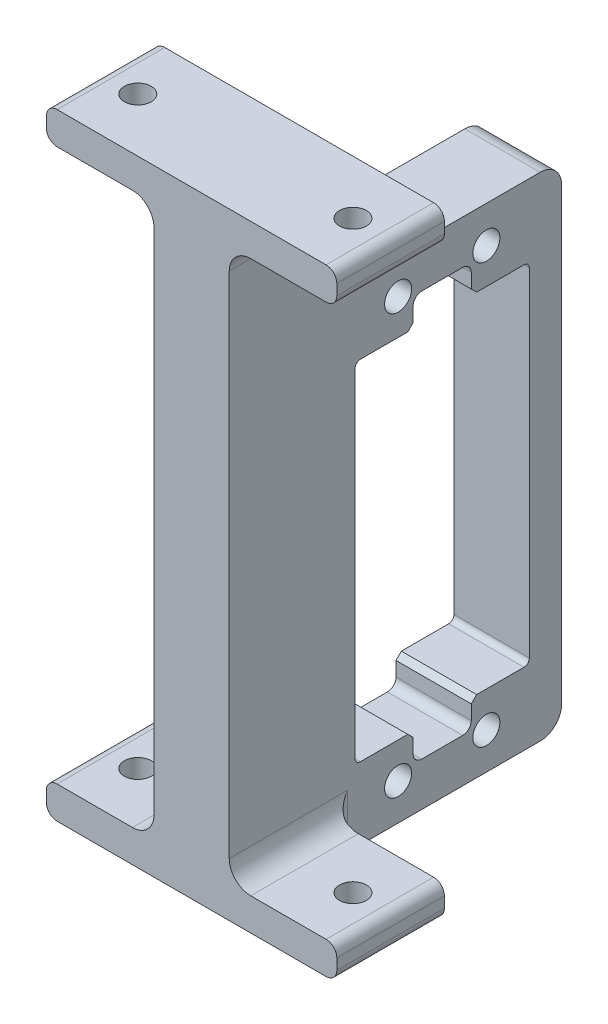
SolidWorks part; units mm, degrees
material "PLA"
ref_plane "Front Plane" through (0, 0, 0) normal (0, 0, 1) x (1, 0, 0)
ref_plane "Top Plane" through (0, 0, 0) normal (0, 1, 0) x (1, 0, 0)
ref_plane "Right Plane" through (0, 0, 0) normal (1, 0, 0) x (0, 0, -1)
sketch "Sketch1" plane through (0, 0, 0) normal (0, 0, 1) x (1, 0, 0)
  line L0 (17.145, 0) -> (-17.145, 0)
  line L1 (-17.145, 0) -> (-17.145, 3.81)
  line L2 (-17.145, 3.81) -> (-4.445, 3.81)
  line L3 (-4.445, 3.81) -> (-4.445, 68.961)
  line L11 (-4.445, 36.3855) -> (4.445, 36.3855) construction
  line L18 (4.445, 3.81) -> (4.445, 68.961)
  line L19 (17.145, 3.81) -> (4.445, 3.81)
  line L20 (17.145, 0) -> (17.145, 3.81)
  line L21 (17.145, 68.961) -> (4.445, 68.961)
  line L22 (17.145, 72.771) -> (17.145, 68.961)
  line L23 (17.145, 72.771) -> (-17.145, 72.771)
  line L24 (-17.145, 72.771) -> (-17.145, 68.961)
  line L25 (-17.145, 68.961) -> (-4.445, 68.961)
  dimension "D1" = 8.89
  dimension "D2" = 3.81
  dimension "D3" = 3.81
  dimension "D4" = 72.771
  dimension "D5" = 34.29
extrude "Frame_Mount" add sketch "Sketch1" along normal blind 12.7
sketch "Sketch3" plane through (0, 0, 0) normal (0, -1, 0) x (1, 0, 0)
  line L0 (17.145, 6.35) -> (-17.145, 6.35) construction
  line L1 (17.145, 12.7) -> (17.145, 0) construction
  line L2 (-17.145, 12.7) -> (-17.145, 0) construction
  line L3 (0, 0) -> (0, 12.7) construction
  line L4 (-17.145, 12.7) -> (17.145, 12.7) construction
  circle A0 centre (12.7, 6.35) radius 1.5875
  circle A1 centre (-12.7, 6.35) radius 1.5875
  dimension "D1" = 3.175
  dimension "D2" = 25.4
extrude "Mount_Holes" cut sketch "Sketch3" against normal through all
sketch "Sketch4" plane through (4.445, 0, 0) normal (1, 0, 0) x (0, 0, -1)
  line L1 (2.159, 49.657) -> (22.733, 49.657)
  line L2 (2.159, 49.657) -> (2.159, 8.509)
  line L3 (2.159, 8.509) -> (22.733, 8.509)
  line L4 (22.733, 49.657) -> (22.733, 8.509)
  line L5 (-12.7, 0) -> (0, 0) construction
  line L6 (0, 58.166) -> (26.543, 58.166)
  line L7 (0, 58.166) -> (0, 0)
  line L8 (0, 0) -> (26.543, 0)
  line L9 (26.543, 58.166) -> (26.543, 0)
  line L10 (0, 3.81) -> (0, 68.961) construction
  line L11 (0, 29.083) -> (2.159, 29.083) construction
  dimension "D1" = 20.574
  dimension "D2" = 41.148
  dimension "D3" = 58.166
  dimension "D5" = 3.81
  dimension "0.2" = 2.159
  dimension "D7" = 0
extrude "Servo_Mount_Feature" add sketch "Sketch4" against normal blind 8.89
sketch "Sketch5" plane through (4.445, 0, 0) normal (1, 0, 0) x (0, 0, -1)
  line L0 (12.446, 49.657) -> (12.446, 58.166) construction
  line L1 (22.733, 49.657) -> (2.159, 49.657) construction
  line L2 (26.543, 58.166) -> (0, 58.166) construction
  line L3 (12.446, 53.848) -> (7.239, 53.848) construction
  line L4 (0, 29.083) -> (22.733, 29.083) construction
  line L5 (0, 8.509) -> (0, 49.657) construction
  line L6 (22.733, 8.509) -> (22.733, 49.657) construction
  circle A4 centre (7.239, 53.848) radius 1.6002
  circle A5 centre (17.653, 53.848) radius 1.6002
  circle A6 centre (17.653, 4.318) radius 1.6002
  circle A7 centre (7.239, 4.318) radius 1.6002
  dimension "D1" = 3.2004
  dimension "D2" = 10.414
  dimension "D3" = 49.53
extrude "Servo_Mount_Holes" cut sketch "Sketch5" against normal through all
fillet "Fillet1" radius 2.54 7 edges at (0, 0, -26.543) (0, 58.166, -26.543) (0, 58.166, 0) (-4.445, 3.81, 6.35) (-4.445, 68.961, 6.35) (4.445, 68.961, 6.35) (4.445, 3.81, 6.35)
fillet "Fillet2" radius 1.27 2 edges at (-4.445, 3.175, 0) (4.445, 3.175, 0)
fillet "Fillet3" radius 0.635 4 edges at (0, 49.657, -22.733) (0, 8.509, -22.733) (0, 8.509, -2.159) (0, 49.657, -2.159)
ref_plane "Servo_Midplane" through (0, 0, -12.446) normal (0, 0, -1) x (-1, 0, 0)
ref_plane "Servo_Midplane2" through (0, 29.083, 0) normal (0, -1, 0) x (-1, 0, 0)
fillet "Fillet4" radius 1.27 8 edges at (-17.145, 3.81, 6.35) (17.145, 3.81, 6.35) (17.145, 0, 6.35) (-17.145, 0, 6.35) (17.145, 68.961, 6.35) (17.145, 72.771, 6.35) (-17.145, 72.771, 6.35) (-17.145, 68.961, 6.35)
sketch "Sketch6" plane through (4.445, 0, 0) normal (1, 0, 0) x (0, 0, -1)
  line L0 (17.653, 53.848) -> (7.239, 53.848) construction
  line L1 (12.446, 53.848) -> (12.446, 4.318) construction
  line L2 (7.239, 4.318) -> (17.653, 4.318) construction
  line L3 (9.017, 49.657) -> (9.017, 53.0098)
  line L4 (22.098, 49.657) -> (2.794, 49.657) construction
  line L5 (9.017, 53.0098) -> (15.875, 53.0098)
  line L6 (9.017, 49.657) -> (15.875, 49.657)
  line L7 (15.875, 49.657) -> (15.875, 53.0098)
  line L8 (12.446, 29.083) -> (22.733, 29.083) construction
  line L9 (22.733, 9.144) -> (22.733, 49.022) construction
  line L10 (15.875, 8.509) -> (15.875, 5.1562)
  line L11 (9.017, 8.509) -> (15.875, 8.509)
  line L12 (9.017, 5.1562) -> (15.875, 5.1562)
  line L13 (9.017, 8.509) -> (9.017, 5.1562)
  point P17 (12.446, 49.657)
  point P18 (12.446, 53.0098)
  point P26 (12.446, 5.1562)
  point P27 (12.446, 8.509)
  dimension "D1" = 6.858
  dimension "D2" = 3.3528
extrude "ServoWire-Gap" cut sketch "Sketch6" against normal through all
fillet "Fillet5" radius 1.016 4 edges at (0, 5.1562, -15.875) (0, 5.1562, -9.017) (0, 53.0098, -15.875) (0, 53.0098, -9.017)
chamfer "Chamfer1" distance 0.635 angle 45 4 edges at (0, 8.509, -9.017) (0, 8.509, -15.875) (0, 49.657, -15.875) (0, 49.657, -9.017)
